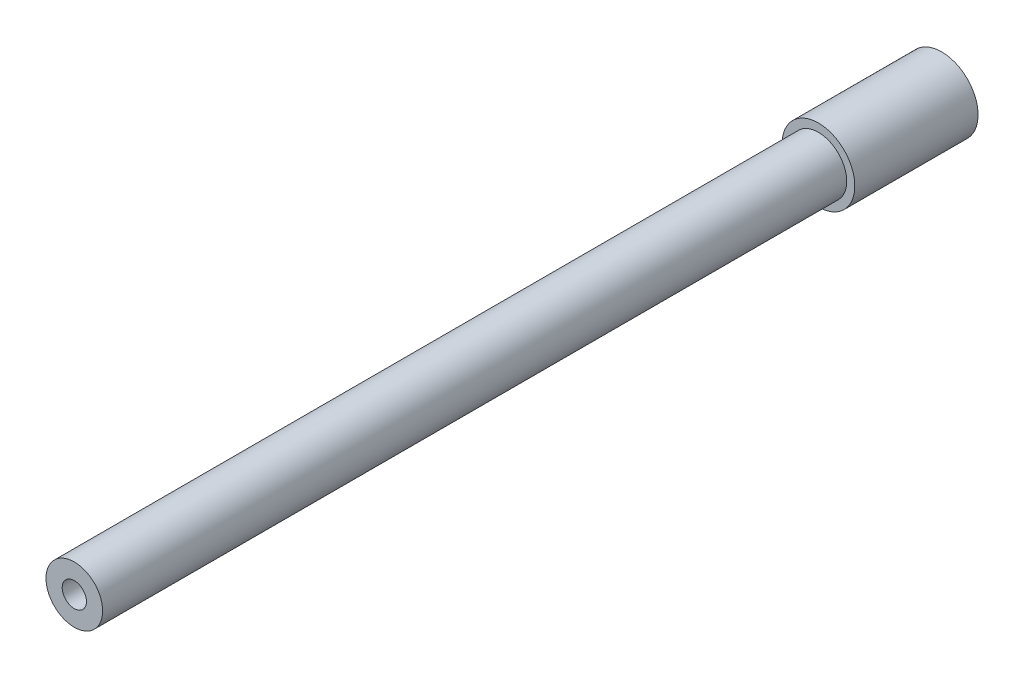
SolidWorks part; units mm, degrees
material "AISI 316 Annealed Stainless Steel Bar (SS)"
ref_plane "Front Plane" through (0, 0, 0) normal (0, 0, 1) x (1, 0, 0)
ref_plane "Top Plane" through (0, 0, 0) normal (0, 1, 0) x (1, 0, 0)
ref_plane "Right Plane" through (0, 0, 0) normal (1, 0, 0) x (0, 0, -1)
sketch "Sketch1" plane through (0, 0, 0) normal (0, 0, 1) x (1, 0, 0)
  circle A0 centre (5.8264, 0) radius 1.75 construction
  circle A1 centre (5.8264, 0) radius 1.75
extrude "Boss-Extrude1" add sketch "Sketch1" along normal blind 53.62
sketch "Sketch3" plane through (0, 0, 53.62) normal (0, 0, 1) x (1, 0, 0)
  circle A0 centre (5.8264, 0) radius 0.75 construction
  circle A1 centre (5.8264, 0) radius 0.75
extrude "Cut-Extrude1" cut sketch "Sketch3" against normal blind 10
sketch "Sketch4" plane through (0, 0, 0) normal (0, 0, -1) x (-1, 0, 0)
  circle A2 centre (-5.8264, 0) radius 2.25
  circle A3 centre (-5.8264, 0) radius 2.25
  dimension "D1" = 0.5
extrude "Boss-Extrude2" add sketch "Sketch4" against normal blind 7.62
